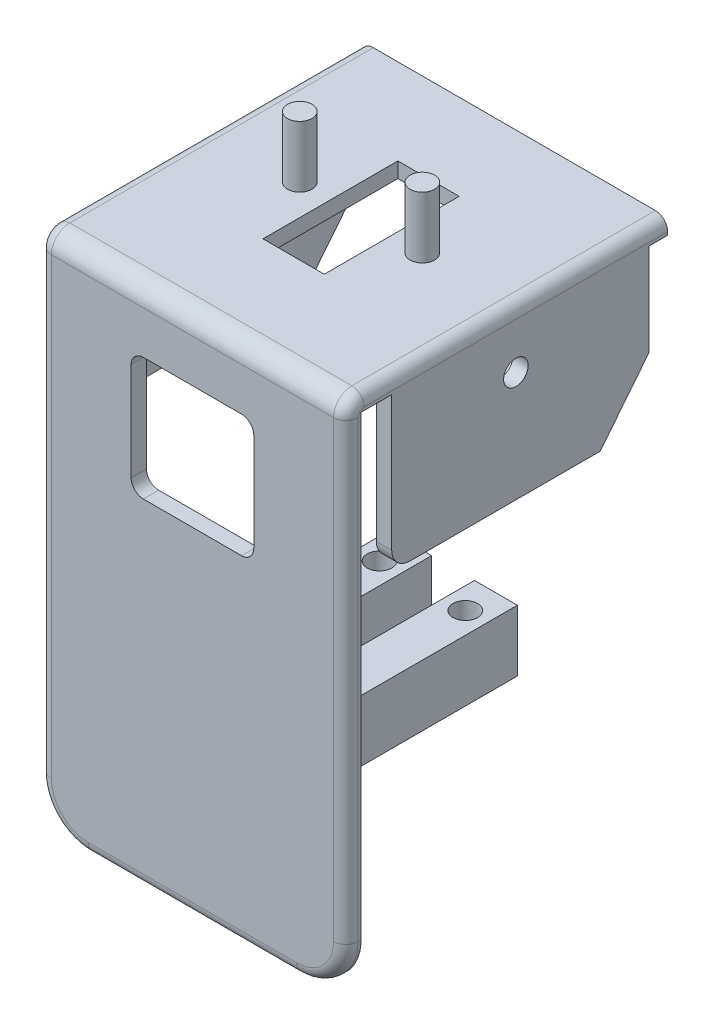
SolidWorks part; units mm, degrees
ref_plane "Alzado" through (0, 0, 0) normal (0, 0, 1) x (1, 0, 0)
ref_plane "Planta" through (0, 0, 0) normal (0, 1, 0) x (1, 0, 0)
ref_plane "Vista lateral" through (0, 0, 0) normal (1, 0, 0) x (0, 0, -1)
sketch "Croquis1" plane through (0, 0, 0) normal (0, 0, 1) x (1, 0, 0)
  line L0 (-25, 42.5) -> (-25, 32.5) construction
  line L1 (17, -42.5) -> (-17, -42.5)
  line L2 (25, -34.5) -> (25, 42.5)
  line L3 (25, 42.5) -> (-25, 42.5)
  line L4 (-25, -34.5) -> (-25, 42.5)
  line L5 (25, -42.5) -> (-25, 42.5) construction
  line L6 (25, 42.5) -> (-25, -42.5) construction
  line L7 (-25, 32.5) -> (-25, 12.5) construction
  line L8 (-25, 32.5) -> (25, 32.5) construction
  line L9 (-25, 12.5) -> (25, 12.5) construction
  line L10 (-25, 12.5) -> (0, 12.5) construction
  line L11 (0, 12.5) -> (0, 32.5) construction
  line L12 (0, 12.5) -> (0, 22.5) construction
  line L14 (8, 12.5) -> (-8, 12.5)
  line L15 (10, 14.5) -> (10, 30.5)
  line L16 (8, 32.5) -> (-8, 32.5)
  line L17 (-10, 14.5) -> (-10, 30.5)
  line L18 (10, 12.5) -> (-10, 32.5) construction
  line L19 (10, 32.5) -> (-10, 12.5) construction
  arc A0 (-17, -42.5) -> (-25, -34.5) centre (-17, -34.5) cw
  arc A1 (17, -42.5) -> (25, -34.5) centre (17, -34.5) ccw
  arc A2 (-8, 32.5) -> (-10, 30.5) centre (-8, 30.5) ccw
  arc A3 (-8, 12.5) -> (-10, 14.5) centre (-8, 14.5) cw
  arc A4 (8, 12.5) -> (10, 14.5) centre (8, 14.5) ccw
  arc A5 (10, 30.5) -> (8, 32.5) centre (8, 30.5) ccw
  point P0 (0, 0)
  dimension "D3" = 8
  dimension "D9" = 2
  dimension "D1" = 85
  dimension "D2" = 50
  dimension "D4" = 10
  dimension "D5" = 20
  dimension "D6" = 10
  dimension "D7" = 20
  dimension "D8" = 20
extrude "Saliente-Extruir1" add sketch "Croquis1" along normal blind 2.5
sketch "Croquis4" plane through (0, 0, 0) normal (0, 0, -1) x (-1, 0, 0)
  line L0 (-25, 42.5) -> (-25, 40)
  line L1 (-25, -34.5) -> (-25, 42.5) construction
  line L2 (-25, 40) -> (25, 40)
  line L3 (25, 42.5) -> (25, -34.5) construction
  line L4 (25, 40) -> (25, 42.5)
  line L5 (25, 42.5) -> (-25, 42.5)
  dimension "D1" = 2.5
extrude "Saliente-Extruir2" add sketch "Croquis4" along normal blind 50
fillet "Redondeo2" radius 3 1 edges at (0, 42.5, 2.5)
sketch "Croquis6" plane through (0, 40, 0) normal (0, -1, 0) x (1, 0, 0)
  line L0 (-25, 0) -> (-25, -5) construction
  line L1 (-25, -50) -> (-25, 0) construction
  line L2 (-25, -5) -> (-22.5, -5)
  line L3 (-22.5, -5) -> (-22.5, -47)
  line L4 (-22.5, -47) -> (-25, -47)
  line L5 (-25, -47) -> (-25, -5)
  line L6 (25, -50) -> (-25, -50) construction
  line L7 (25, -5) -> (22.5, -5)
  line L8 (25, -50) -> (25, 0) construction
  line L9 (22.5, -5) -> (22.5, -47)
  line L10 (22.5, -47) -> (25, -47)
  line L11 (25, -47) -> (25, -5)
  dimension "D1" = 5
  dimension "D2" = 3
  dimension "D3" = 2.5
  dimension "D4" = 2.5
extrude "Saliente-Extruir3" add sketch "Croquis6" along normal blind 25
fillet "Redondeo3" radius 2 9 edges at (-25, 41.6213, 1.6213) (-25, 2.5, 2.5) (-22.6569, -40.1569, 2.5) (0, -42.5, 2.5) (22.6569, -40.1569, 2.5) (25, 2.5, 2.5) (25, 41.6213, 1.6213) (-25, 42.5, -25.25) (25, 42.5, -25.25)
sketch "Croquis7" plane through (25, 0, 0) normal (1, 0, 0) x (0, 0, -1)
  line L0 (39, 15) -> (47, 25)
  line L1 (47, 15) -> (5, 15) construction
  line L2 (47, 15) -> (47, 40) construction
  line L3 (47, 25) -> (47, 15)
  line L4 (47, 15) -> (39, 15)
  line L9 (5, 18) -> (5, 15)
  line L10 (5, 15) -> (8, 15)
  arc A0 (5, 18) -> (8, 15) centre (8, 18) ccw
  point P16 (5, 15)
  dimension "D3" = 3
  dimension "D1" = 8
  dimension "D2" = 10
extrude "Cortar-Extruir1" cut sketch "Croquis7" against normal blind 25
sketch "Croquis8" plane through (-25, 0, 0) normal (-1, 0, 0) x (0, 0, 1)
  line L0 (-39, 15) -> (-47, 15)
  line L1 (-5, 15) -> (-47, 15) construction
  line L2 (-47, 15) -> (-47, 25)
  line L3 (-47, 15) -> (-47, 40) construction
  line L4 (-47, 25) -> (-39, 15)
  line L5 (-5, 18) -> (-5, 15)
  line L7 (-5, 15) -> (-8, 15)
  arc A0 (-5, 18) -> (-8, 15) centre (-8, 18) cw
  point P16 (-5, 15)
  dimension "D3" = 3
  dimension "D1" = 10
  dimension "D2" = 8
extrude "Cortar-Extruir2" cut sketch "Croquis8" against normal blind 25
sketch "Croquis11" plane through (0, 40, 0) normal (0, -1, 0) x (1, 0, 0)
  line L0 (-25, 0) -> (0, 0) construction
  line L1 (25, 0) -> (-25, 0) construction
  line L2 (0, 0) -> (0, -50) construction
  line L3 (25, -50) -> (-25, -50) construction
  line L5 (5, -36) -> (-5, -36)
  line L6 (5, -36) -> (5, -14)
  line L7 (5, -14) -> (-5, -14)
  line L8 (-5, -36) -> (-5, -14)
  line L9 (5, -36) -> (-5, -14) construction
  line L10 (5, -14) -> (-5, -36) construction
  point P5 (0, -25)
  dimension "D1" = 22
  dimension "D2" = 10
extrude "Cortar-Extruir3" cut sketch "Croquis11" against normal blind 25
sketch "Croquis12" plane through (-25, 0, 0) normal (-1, 0, 0) x (0, 0, 1)
  line L0 (-50, 40.5) -> (-25.25, 40.5) construction
  line L1 (-0.5, 40.5) -> (-50, 40.5) construction
  line L2 (-25.25, 40.5) -> (-25.25, 33) construction
  circle A0 centre (-25.25, 33) radius 2
  dimension "D1" = 7.5
extrude "Cortar-Extruir4" cut sketch "Croquis12" against normal blind 25
sketch "Croquis13" plane through (25, 0, 0) normal (1, 0, 0) x (0, 0, -1)
  line L0 (50, 40.5) -> (25.25, 40.5) construction
  line L1 (50, 40.5) -> (0.5, 40.5) construction
  line L2 (25.25, 40.5) -> (25.25, 33) construction
  circle A0 centre (25.25, 33) radius 2
  dimension "D1" = 7.5
extrude "Cortar-Extruir5" cut sketch "Croquis13" against normal blind 25
sketch "Croquis14" plane through (0, 42.5, 0) normal (0, 1, 0) x (1, 0, 0)
  line L0 (-5, 36) -> (-5, 25) construction
  line L1 (-5, 14) -> (-5, 36) construction
  line L2 (-5, 25) -> (-10, 25) construction
  line L3 (5, 14) -> (5, 25) construction
  line L4 (5, 14) -> (-5, 14) construction
  line L5 (5, 36) -> (5, 14) construction
  line L6 (5, 25) -> (10, 25) construction
  circle A0 centre (-10, 25) radius 2
  circle A1 centre (10, 25) radius 2
  dimension "D3" = 20
  dimension "D1" = 5
  dimension "D2" = 5
extrude "Saliente-Extruir4" add sketch "Croquis14" along normal blind 10
sketch "Croquis15" plane through (0, 0, 0) normal (0, 0, -1) x (-1, 0, 0)
  line L0 (-25, -34.5) -> (-25, -24.5) construction
  line L1 (-25, -34.5) -> (-25, 40) construction
  line L2 (0, -42.5) -> (0, -24.5) construction
  line L3 (25, 40) -> (25, -34.5) construction
  line L4 (-25, -24.5) -> (-10.5, -24.5) construction
  line L5 (-10.5, -24.5) -> (-10.5, -14.5)
  line L6 (-10.5, -14.5) -> (-3.5, -14.5)
  line L7 (-3.5, -14.5) -> (-3.5, -24.5)
  line L8 (-3.5, -24.5) -> (-10.5, -24.5)
  line L9 (25, -24.5) -> (10.5, -24.5) construction
  line L10 (10.5, -24.5) -> (3.5, -24.5)
  line L11 (3.5, -24.5) -> (3.5, -14.5)
  line L12 (3.5, -14.5) -> (10.5, -14.5)
  line L13 (10.5, -14.5) -> (10.5, -24.5)
  line L14 (17, -42.5) -> (-17, -42.5) construction
  line L15 (0, -24.5) -> (-3.5, -24.5) construction
  line L16 (0, -24.5) -> (3.5, -24.5) construction
  line L17 (-3.5, -14.5) -> (-3.5, -19.5) construction
  line L18 (-3.5, -19.5) -> (3.5, -19.5) construction
  point P21 (0, -19.5)
  dimension "D1" = 10
  dimension "D2" = 7
  dimension "D3" = 7
  dimension "D4" = 10
  dimension "D7" = 10
  dimension "D8" = 3.5
  dimension "D9" = 3.5
extrude "Saliente-Extruir5" add sketch "Croquis15" along normal blind 40
sketch "Croquis17" plane through (0, -14.5, 0) normal (0, 1, 0) x (1, 0, 0)
  line L0 (-10.5, 40) -> (-7, 40) construction
  line L1 (-10.5, 40) -> (-3.5, 40) construction
  line L2 (-7, 40) -> (-7, 35) construction
  circle A0 centre (-7, 35) radius 2
  dimension "D1" = 5
extrude "Cortar-Extruir6" cut sketch "Croquis17" against normal blind 50
sketch "Croquis18" plane through (0, -14.5, 0) normal (0, 1, 0) x (1, 0, 0)
  line L0 (3.5, 40) -> (7, 40) construction
  line L1 (3.5, 40) -> (10.5, 40) construction
  line L2 (7, 40) -> (7, 35) construction
  circle A0 centre (7, 35) radius 2
  dimension "D1" = 5
extrude "Cortar-Extruir7" cut sketch "Croquis18" against normal blind 50
